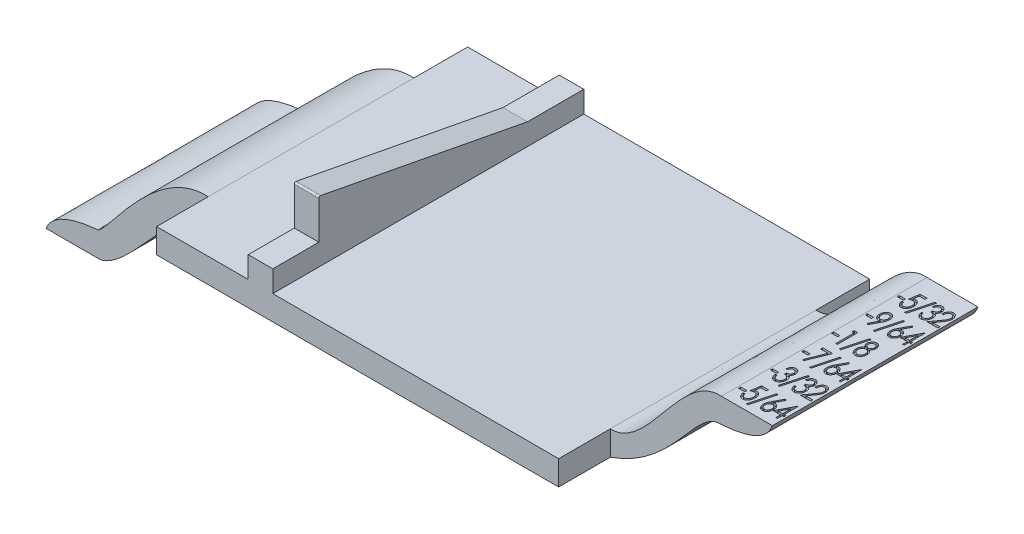
SolidWorks part; units mm, degrees
material "ABS"
ref_plane "Front Plane" through (0, 0, 0) normal (0, 0, 1) x (1, 0, 0)
ref_plane "Top Plane" through (0, 0, 0) normal (0, 1, 0) x (1, 0, 0)
ref_plane "Right Plane" through (0, 0, 0) normal (1, 0, 0) x (0, 0, -1)
other "Configuration Table"
sketch "Sketch1" plane through (0, 0, 0) normal (0, 0, 1) x (1, 0, 0)
  line L0 (0, 0) -> (0, 1.2) construction
  line L1 (0, -55) -> (0, 55) construction
  line L2 (0, 0) -> (0, -1.2) construction
  line L3 (0, 0) -> (35.5, 0) construction
  line L4 (55, 0) -> (-55, 0) construction
  line L5 (0, 0) -> (-35.5, 0) construction
  line L6 (0, 0) -> (27.9685, 4.9316) construction
  line L7 (0, 0) -> (-27.9685, -4.9316) construction
  line L8 (1.1, -1.2) -> (19.65, -1.2) construction
  line L9 (-1.1, -1.2) -> (-19.65, -1.2) construction
  line L10 (0, 1.2) -> (-8.2914, 1.2) construction
  line L11 (0, 1.2) -> (19.65, 1.2) construction
  line L12 (-19.65, -1.2) -> (-19.65, 1.2) construction
  line L13 (19.65, -1.2) -> (19.65, 1.2) construction
  line L14 (19.65, -1.2) -> (19.65, 10.7) construction
  line L15 (0, 0) -> (-10.6914, 0) construction
  line L16 (-19.65, 1.2) -> (-10.6914, 1.2)
  line L17 (-19.65, 1.2) -> (-19.65, -1.2)
  line L18 (-19.65, -1.2) -> (-1.1, -1.2)
  line L19 (19.65, 1.2) -> (19.65, -1.2)
  line L20 (-10.6914, 0) -> (-10.6914, -1.2) construction
  line L21 (-10.6914, -1.2) -> (-10.6914, 7.2) construction
  line L22 (-10.6914, 7.2) -> (-8.2914, 7.2) construction
  line L23 (-8.2914, 7.2) -> (-8.2914, 1.2) construction
  line L24 (0, 1.2) -> (0, -5) construction
  line L25 (0, -5) -> (-1.1, -5) construction
  line L26 (-1.1, -5) -> (-1.1, -1.2) construction
  line L27 (0, -5) -> (1.1, -5) construction
  line L28 (1.1, -5) -> (1.1, -1.2) construction
  line L29 (-8.2914, 1.2) -> (-8.2914, 7.2)
  line L30 (-8.2914, 7.2) -> (-10.6914, 7.2)
  line L31 (-10.6914, 7.2) -> (-10.6914, 1.2)
  line L32 (-1.1, -1.2) -> (-1.1, -5)
  line L33 (-1.1, -5) -> (1.1, -5)
  line L34 (1.1, -5) -> (1.1, -1.2)
  line L35 (-10.6914, 1.2) -> (-19.65, 1.2) construction
  line L36 (-8.2914, 1.2) -> (19.65, 1.2)
  line L37 (1.1, -1.2) -> (19.65, -1.2)
extrude "Boss-Extrude1" add sketch "Sketch1" along normal blind 30.4
sketch "Sketch2" plane through (0, 0, 0) normal (1, 0, 0) x (0, 0, -1)
  line L0 (0, 0) -> (0, 1.2) construction
  line L1 (0, 6.71) -> (0, -6.71) construction
  line L2 (-30.4, 1.2) -> (0, 1.2) construction
  line L3 (0, 1.2) -> (0, 3.3) construction
  line L4 (0, 3.3) -> (-4.5, 3.3) construction
  line L5 (-4.5, 3.3) -> (-4.5, 7.0186) construction
  line L6 (-30.4, 7.2) -> (0, 7.2) construction
  line L7 (-30.4, 1.2) -> (-30.4, 3.3) construction
  line L8 (-30.4, 1.2) -> (-30.4, 7.2) construction
  line L9 (-30.4, 3.3) -> (-24.9, 3.3) construction
  line L10 (-24.9, 3.3) -> (-4.6782, 7.1659) construction
  line L11 (-24.9, 3.3) -> (-30.4, 3.3)
  line L12 (-30.4, 3.3) -> (-30.4, 7.2)
  line L13 (-30.4, 7.2) -> (0, 7.2)
  line L14 (0, 7.2) -> (0, 3.3)
  line L15 (0, 3.3) -> (-4.5, 3.3)
  line L16 (-4.5, 3.3) -> (-4.5, 7.0186)
  line L17 (-24.9, 3.3) -> (-4.6782, 7.1659)
  line L18 (-30.4, 1.2) -> (-30.4, 3.3) construction
  arc A0 (-4.5, 7.0186) -> (-4.6782, 7.1659) centre (-4.65, 7.0186) ccw
  point P20 (-4.5, 7.2)
  dimension "D1" = 0.15
sketch "Sketch3" plane through (0, 0, 0) normal (1, 0, 0) x (0, 0, -1)
  line L0 (-30.4, 1.2) -> (-30.4, 3.3) construction
  line L1 (-30.4, 3.3) -> (-25.9, 3.3)
  line L2 (-24.9, 3.3) -> (-30.4, 3.3) construction
  line L3 (-25.9, 3.3) -> (-25.9, 7.0186)
  line L4 (-30.4, 7.2) -> (0, 7.2) construction
  line L5 (0, 1.2) -> (0, 3.3) construction
  line L6 (0, 3.3) -> (-5.5, 3.3) construction
  line L7 (-5.5, 3.3) -> (-25.7218, 7.1659) construction
  line L8 (-30.4, 3.3) -> (-30.4, 7.2)
  line L9 (-30.4, 7.2) -> (0, 7.2)
  line L10 (0, 7.2) -> (0, 3.3)
  line L11 (0, 3.3) -> (-5.5, 3.3)
  line L12 (-5.5, 3.3) -> (-25.7218, 7.1659)
  arc A0 (-25.7218, 7.1659) -> (-25.9, 7.0186) centre (-25.75, 7.0186) ccw
  point P17 (-25.9, 7.2)
  dimension "D1" = 0.15
extrude "Cut-Extrude1" cut sketch "Sketch3" against normal blind 30.4
sketch "Sketch4" plane through (0, 0, 0) normal (1, 0, 0) x (0, 0, -1)
  line L0 (-30.4, -1.2) -> (0, -1.2) construction
  line L1 (0, 6.6927) -> (0, -6.6927) construction
  line L2 (-30.4, -1.2) -> (0, -1.2) construction
  line L3 (0, -1.2) -> (-15.2, -1.2) construction
  line L4 (-15.2, -1.2) -> (-25.8, -1.2) construction
  line L5 (-15.2, -1.2) -> (-4.6, -1.2) construction
  line L7 (-4.6, -1.2) -> (-4.6, -3)
  line L10 (-25.8, -1.2) -> (-30.4, -1.2)
  line L11 (-30.4, -1.2) -> (-30.4, -5.0074)
  line L12 (-4.6, -1.2) -> (0, -1.2)
  line L13 (0, -1.2) -> (0, -5)
  line L14 (-30.4, -5) -> (0, -5) construction
  line L15 (0, -5) -> (-24.298, -5)
  line L16 (-24.298, -5) -> (-24.298, -5.3755)
  line L17 (-24.298, -5.3755) -> (-26.3295, -5.3755)
  line L18 (-26.3295, -5.3755) -> (-26.3295, -5)
  line L19 (-26.3295, -5) -> (-30.4, -5.0074)
  line L21 (-4.6, -3) -> (-13.3, -3) construction
  line L22 (-13.3, -3) -> (-4.6, -3)
  line L23 (-25.8, -1.2) -> (-25.55, -1.2) construction
  line L27 (-25.8, -1.2) -> (-25.55, -1.2)
  line L28 (-25.55, -1.2) -> (-25.3, -1.2)
  line L29 (-25.3, -1.2) -> (-25.3, -3.407)
  line L30 (-24.7606, -3.9054) -> (-13.3, -3)
  arc A2 (-25.3, -3.407) -> (-24.7606, -3.9054) centre (-24.8, -3.407) ccw
  dimension "D1" = 0.5
extrude "Cut-Extrude2" cut sketch "Sketch4" along normal blind 30.4 and the other way blind 30.4
sketch "Sketch5" plane through (0, 0, 0) normal (0, 0, 1) x (1, 0, 0)
  line L0 (0, 0) -> (-35.5096, 0) construction
  line L1 (16.72, 0) -> (-16.72, 0) construction
  line L2 (-35.5096, 1.2) -> (-35.5096, -9.4081) construction
  line L3 (0, 0) -> (0, 1.2) construction
  line L4 (0, -6.6927) -> (0, 6.6927) construction
  line L5 (19.65, 1.2) -> (-8.2914, 1.2) construction
  line L6 (0, 1.2) -> (-35.5096, 1.2) construction
  line L7 (0, -1.2) -> (35.486, -1.2) construction
  line L8 (-19.65, -1.2) -> (19.65, -1.2) construction
  line L9 (35.486, -1.2) -> (35.486, 9.3879) construction
  line L10 (-35.5096, -9.4081) -> (35.486, 9.3879) construction
  line L11 (0, 0) -> (35.486, 0) construction
  line L12 (-35.5096, -9.4081) -> (-30.4848, -9.4081) construction
  line L13 (-35.5096, -9.4081) -> (-35.5096, -6.9985) construction
  line L14 (-35.5096, -6.9985) -> (-30.4848, -6.9985) construction
  line L15 (-30.4848, -6.9985) -> (-30.4848, -9.4081) construction
  line L16 (35.486, 9.3879) -> (30.5056, 9.3879) construction
  line L17 (30.5056, 9.3879) -> (30.5056, 6.9935) construction
  line L18 (30.5056, 6.9935) -> (35.486, 6.9935) construction
  line L19 (-30.4848, -9.4081) -> (-19.65, -1.2) construction
  line L20 (-30.4848, -6.9985) -> (-19.65, 1.2) construction
  line L21 (30.5056, 9.3879) -> (19.65, 1.2) construction
  line L22 (30.5056, 6.9935) -> (19.65, -1.2) construction
  line L23 (-35.5096, -9.4081) -> (-30.4848, -9.4081)
  line L24 (-19.65, 1.2) -> (-19.65, -1.2)
  line L25 (30.5056, 9.3879) -> (35.486, 9.3879)
  line L26 (19.65, -1.2) -> (19.65, 1.2)
  spline S0 degree 2 poles (30.5056, 6.9935) (34.7583, 7.2794) (35.486, 9.3879) knots 0 0 0 1 1 1
  spline S1 degree 2 poles (-30.4848, -6.9985) (-34.6979, -7.3948) (-35.5096, -9.4081) knots 0 0 0 1 1 1
  spline S2 degree 3 poles (-30.4848, -9.4081) (-27.6154, -9.536) (-22.4046, -0.0308) (-19.65, -1.2) knots 0 0 0 0 1 1 1 1
  spline S3 degree 3 poles (-30.4848, -6.9985) (-29.7121, -7.1294) (-24.9614, 1.4659) (-19.65, 1.2) knots 0 0 0 0 1 1 1 1
  spline S4 degree 3 poles (19.65, 1.2) (23.3491, 1.0364) (26.532, 9.6466) (30.5056, 9.3879) knots 0 0 0 0 1 1 1 1
  spline S5 degree 3 poles (19.65, -1.2) (26.016, 0.9893) (27.8696, 7.1515) (30.5056, 6.9935) knots 0 0 0 0 1 1 1 1
extrude "Boss-Extrude2" add sketch "Sketch5" along normal blind 25.35
sketch "Sketch6" plane through (0, 0, 0) normal (0, 1, 0) x (1, 0, 0)
  line L0 (-19.65, -30.4) -> (-19.65, 0) construction
  line L1 (-6.0916, 0) -> (6.0916, 0) construction
  line L2 (-19.65, -25.35) -> (-19.65, 0) construction
  line L3 (-19.65, 0) -> (-19.65, -5.25) construction
  line L4 (19.65, -30.4) -> (19.65, 0) construction
  line L5 (19.65, -25.35) -> (19.65, 0) construction
  line L6 (19.65, 0) -> (19.65, -5.25) construction
  line L7 (-35.5096, -25.35) -> (-35.5096, 0) construction
  line L8 (-19.65, -5.25) -> (-35.5096, -5.25)
  line L9 (-19.65, -5.25) -> (-19.65, 0)
  line L10 (-19.65, 0) -> (-35.5096, 0)
  line L11 (-35.5096, -5.25) -> (-35.5096, 0)
  line L12 (35.486, -25.35) -> (35.486, 0) construction
  line L13 (19.65, -5.25) -> (35.486, -5.25)
  line L14 (19.65, -5.25) -> (19.65, 0)
  line L15 (19.65, 0) -> (35.486, 0)
  line L16 (35.486, -5.25) -> (35.486, 0)
extrude "Cut-Extrude3" cut sketch "Sketch6" against normal blind 26 and the other way blind 26
ref_plane "6HexSizing" through (0, 9.3879, 0) normal (0, 1, 0) x (1, 0, 0)
sketch "Sketch7" plane through (0, 9.3879, 0) normal (0, 1, 0) x (1, 0, 0)
  line L0 (30.5056, -25.35) -> (35.486, -25.35) construction
  line L1 (35.486, -25.35) -> (35.486, -5.25) construction
  line L2 (35.486, -5.25) -> (35.486, -6.1) construction
  line L3 (35.486, -6.1) -> (30.5056, -6.1) construction
  line L4 (30.5056, -25.35) -> (30.5056, -5.25) construction
  line L5 (35.486, -25.35) -> (35.486, -24.5) construction
  line L6 (35.486, -24.5) -> (30.5056, -24.5) construction
  line L7 (30.5056, -6.1) -> (30.5056, -24.5) construction
  line L8 (30.5056, -24.5) -> (30.5056, -15.3) construction
  line L9 (30.5056, -15.3) -> (35.486, -15.3) construction
  line L10 (35.486, -21.4) -> (30.5056, -21.4) construction
  line L11 (35.486, -18.3) -> (30.5056, -18.3) construction
  line L12 (35.486, -15.2) -> (30.5056, -15.2) construction
  line L13 (35.486, -12.1) -> (30.5056, -12.1) construction
  line L14 (35.486, -9) -> (30.5056, -9) construction
  text T0 "-5/64\r\n" font "Century Gothic" height 2
  text T1 "-3/32" font "Century Gothic" height 2
  text T2 "-7/64" font "Century Gothic" height 2
  text T3 "-1/8" font "Century Gothic" height 2
  text T4 "-9/64" font "Century Gothic" height 2
  text T5 "-5/32" font "Century Gothic" height 2
  dimension "D1" = 6
extrude "Cut-Extrude4" cut sketch "Sketch7" against normal blind 0.25
ref_plane "Plane2" through (0, -9.4081, 0) normal (0, -1, 0) x (-1, 0, 0)
sketch "Sketch8" plane through (0, -9.4081, 0) normal (0, -1, 0) x (-1, 0, 0)
  line L0 (30.4848, -25.35) -> (35.5096, -25.35) construction
  line L1 (35.5096, -25.35) -> (35.5096, -5.25) construction
  line L2 (35.5096, -5.25) -> (30.4848, -5.25) construction
  line L3 (30.4848, -5.25) -> (30.4848, -25.35) construction
  line L4 (30.4848, -25.35) -> (32.9972, -25.35) construction
  line L5 (32.9972, -25.35) -> (32.9972, -5.25) construction
  line L6 (30.4848, -15.3) -> (35.5096, -15.3) construction
  line L7 (30.4848, -15.3) -> (30.4848, -9.7) construction
  line L8 (30.4848, -9.7) -> (35.5096, -9.7) construction
  line L9 (30.4848, -15.3) -> (30.4848, -20.7) construction
  line L10 (30.4848, -20.7) -> (35.5096, -20.7) construction
  line L11 (30.4848, -10.7) -> (35.5096, -10.7) construction
  line L12 (30.4848, -16.3) -> (35.5096, -16.3) construction
  line L13 (30.4848, -21.7) -> (35.5096, -21.7) construction
  text T0 "-3/16" font "Century Gothic" height 2
  text T1 "-7/32" font "Century Gothic" height 2
  text T2 "-1/4" font "Century Gothic" height 2
  dimension "D1" = 1
extrude "Cut-Extrude5" cut sketch "Sketch8" against normal blind 0.25
